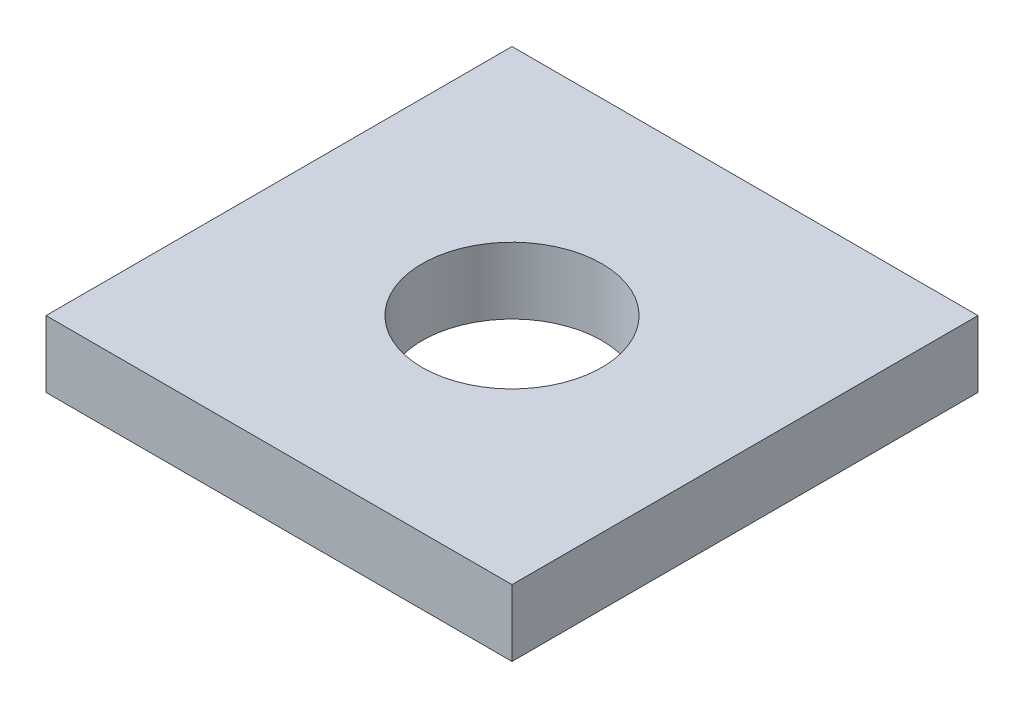
SolidWorks part; units mm, degrees
ref_plane "前视基准面" through (0, 0, 0) normal (0, 0, 1) x (1, 0, 0)
ref_plane "上视基准面" through (0, 0, 0) normal (0, 1, 0) x (1, 0, 0)
ref_plane "右视基准面" through (0, 0, 0) normal (1, 0, 0) x (0, 0, -1)
other "Configuration Table"
sketch "草图1" plane through (0, 0, 0) normal (0, 1, 0) x (1, 0, 0)
  line L7 (-3.5, 3.5) -> (3.5, 3.5)
  line L8 (-3.5, 3.5) -> (-3.5, -3.5)
  line L9 (-3.5, -3.5) -> (3.5, -3.5)
  line L10 (3.5, 3.5) -> (3.5, -3.5)
  line L11 (-3.5, 3.5) -> (3.5, -3.5) construction
  line L12 (-3.5, -3.5) -> (3.5, 3.5) construction
  circle A0 centre (0, 0) radius 1.35
  point P0 (0, 0)
  point P1 (0, 0)
  point P2 (0, 0)
  point P3 (0, 0)
  point P5 (0, 0)
  dimension "D1" = 2.7
  dimension "D4" = 7
extrude "凸台-拉伸1" add sketch "草图1" along normal blind 1
